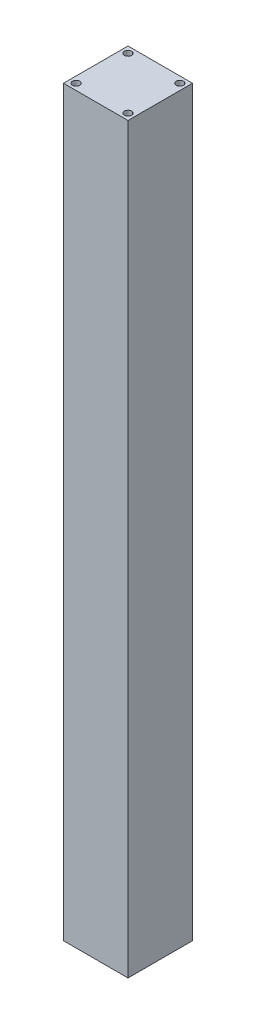
SolidWorks part; units mm, degrees
ref_plane "Front Plane" through (0, 0, 0) normal (0, 0, 1) x (1, 0, 0)
ref_plane "Top Plane" through (0, 0, 0) normal (0, 1, 0) x (1, 0, 0)
ref_plane "Right Plane" through (0, 0, 0) normal (1, 0, 0) x (0, 0, -1)
sketch "Sketch3" plane through (0, 0, 0) normal (0, 1, 0) x (1, 0, 0)
  line L1 (0, 0) -> (75, 0)
  line L2 (0, 0) -> (0, 75)
  line L3 (0, 75) -> (75, 75)
  line L4 (75, 0) -> (75, 75)
  dimension "D1" = 75
  dimension "D2" = 75
extrude "Boss-Extrude1" add sketch "Sketch3" along normal blind 863.6
sketch "Sketch4" plane through (0, 0, 0) normal (0, 1, 0) x (1, 0, 0)
  line L0 (0, 37.5) -> (75, 37.5) construction
  line L1 (0, 75) -> (0, 0) construction
  line L2 (75, 0) -> (75, 75) construction
  line L3 (37.5, 75) -> (37.5, 0) construction
  line L4 (75, 75) -> (0, 75) construction
  line L5 (0, 0) -> (75, 0) construction
  line L6 (7.3375, 67.6625) -> (67.6625, 7.3375) construction
  circle A0 centre (7.3375, 67.6625) radius 4.2333
  circle A1 centre (67.6625, 67.6625) radius 4.2333
  circle A2 centre (7.3375, 7.3375) radius 4.2333
  circle A3 centre (67.6625, 7.3375) radius 4.2333
  point P20 (37.5, 37.5)
  point P21 (37.5, 37.5)
extrude "Cut-Extrude1" cut sketch "Sketch4" against normal blind 25.4 from surface at 863.6 starting at face at (37.5, 863.6, -37.5)
